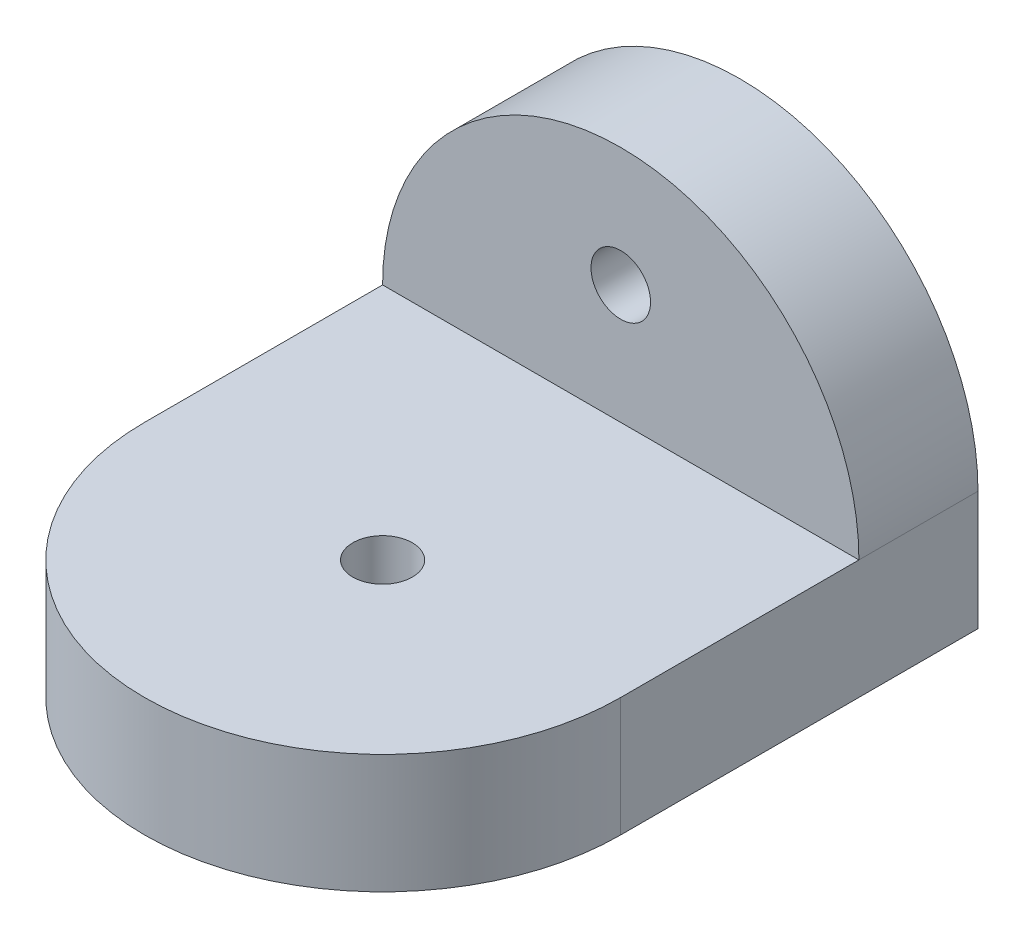
SolidWorks part; units mm, degrees
material "1060 Alaşım"
ref_plane "Ön Düzlem" through (0, 0, 0) normal (0, 0, 1) x (1, 0, 0)
ref_plane "Üst Düzlem" through (0, 0, 0) normal (0, 1, 0) x (1, 0, 0)
ref_plane "Sağ Düzlem" through (0, 0, 0) normal (1, 0, 0) x (0, 0, -1)
sketch "Çizim1" plane through (0, 0, 0) normal (0, 0, 1) x (1, 0, 0)
  line L0 (0, 0) -> (20, 0)
  arc A0 (0, 0) -> (20, 0) centre (10, 0) cw
  dimension "D1" = 10
extrude "Yükseklik-Ekstrüzyon1" add sketch "Çizim1" along normal blind 5
sketch "Çizim2" plane through (0, 0, 0) normal (0, -1, 0) x (1, 0, 0)
  line L0 (0, 15) -> (0, 0)
  line L1 (0, 0) -> (20, 0)
  line L2 (20, 0) -> (20, 15)
  arc A0 (0, 15) -> (20, 15) centre (10, 15) cw
  point P5 (10, 0)
  dimension "D1" = 10
  dimension "D2" = 15
extrude "Yükseklik-Ekstrüzyon2" add sketch "Çizim2" along normal blind 5
sketch "Çizim3" plane through (0, 0, 5) normal (0, 0, 1) x (1, 0, 0)
  line L0 (20, 0) -> (0, 0) construction
  circle A0 centre (10, 5) radius 1.25
  arc A1 (20, 0) -> (0, 0) centre (10, 0) ccw construction
  point P6 (10, 10)
  dimension "D1" = 2.5
  dimension "D2" = 5
extrude "Kes-Ekstrüzyon1" cut sketch "Çizim3" against normal blind 5
sketch "Çizim4" plane through (0, 0, 0) normal (0, 1, 0) x (1, 0, 0)
  line L1 (20, 0) -> (0, 0) construction
  circle A0 centre (10, -15) radius 1.25
  arc A1 (0, -15) -> (20, -15) centre (10, -15) ccw construction
  point P5 (10, -25)
  dimension "D1" = 2.5
  dimension "D2" = 15
extrude "Kes-Ekstrüzyon2" cut sketch "Çizim4" against normal blind 5
